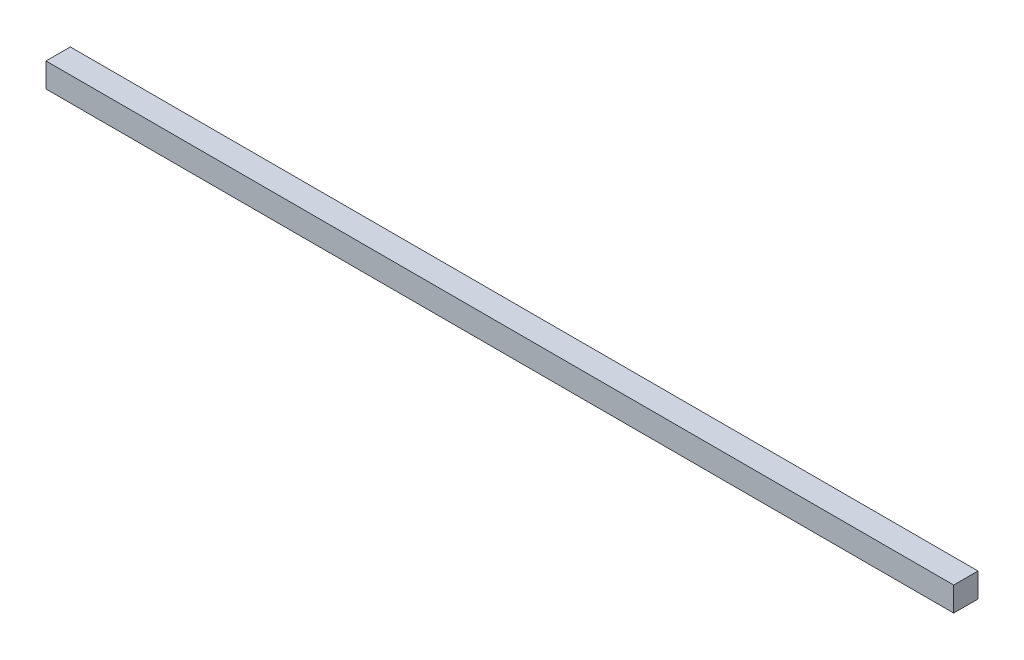
SolidWorks part; units mm, degrees
ref_plane "Front Plane" through (0, 0, 0) normal (0, 0, 1) x (1, 0, 0)
ref_plane "Top Plane" through (0, 0, 0) normal (0, 1, 0) x (1, 0, 0)
ref_plane "Right Plane" through (0, 0, 0) normal (1, 0, 0) x (0, 0, -1)
sketch "Sketch1" plane through (0, 0, 0) normal (1, 0, 0) x (0, 0, -1)
  line L1 (0, 0) -> (38.1, 0)
  line L2 (0, 0) -> (0, -38.1)
  line L3 (0, -38.1) -> (38.1, -38.1)
  line L4 (38.1, 0) -> (38.1, -38.1)
  dimension "D1" = 38.1
  dimension "D2" = 38.1
extrude "Boss-Extrude1" add sketch "Sketch1" along normal blind 1422.4
